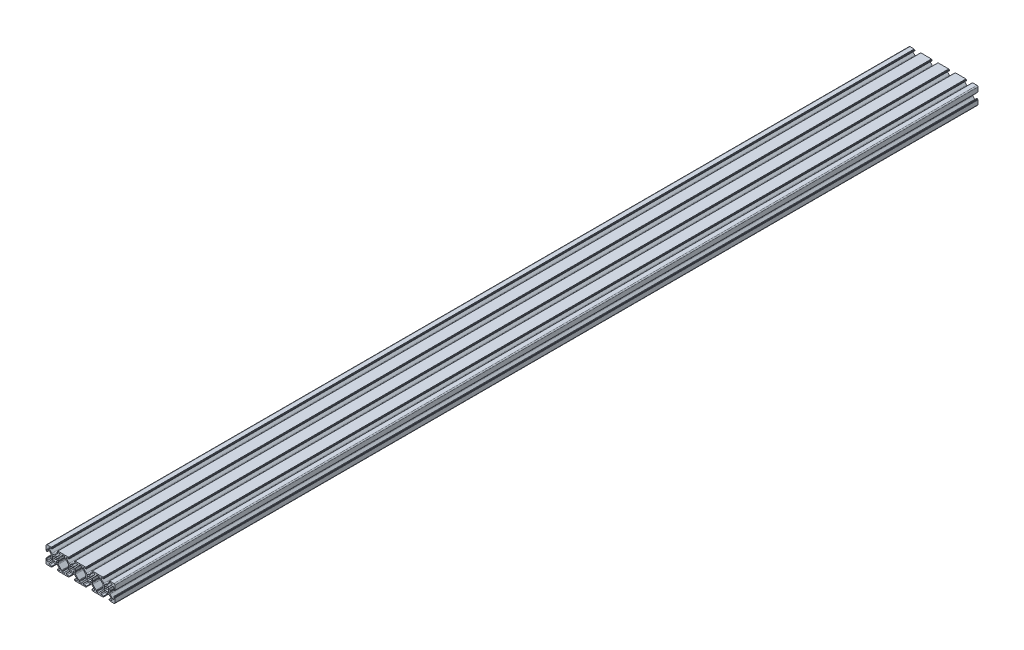
SolidWorks part; units mm, degrees
material "6063-T5"
ref_plane "Ön Düzlem" through (0, 0, 0) normal (0, 0, 1) x (1, 0, 0)
ref_plane "Üst Düzlem" through (0, 0, 0) normal (0, 1, 0) x (1, 0, 0)
ref_plane "Sağ Düzlem" through (0, 0, 0) normal (1, 0, 0) x (0, 0, -1)
sketch "Model" plane through (0, 0, 0) normal (0, 0, 1) x (1, 0, 0)
  line L0 (-8.8, -10) -> (-3.95, -10)
  line L1 (-3.95, -10) -> (-3.95, -9.5)
  line L2 (-3.95, -9.5) -> (-3.1475, -9.5)
  line L3 (-3.1475, -9.5) -> (-3.1475, -8.6)
  line L4 (-3.1475, -8.6) -> (-5.6787, -8.6)
  line L5 (-6.2444, -7.2343) -> (-3.1787, -4.1687)
  line L6 (-0.29, -4.19) -> (0, -3.9)
  line L7 (0, -3.9) -> (0.29, -4.19)
  line L8 (3.1768, -4.1667) -> (6.2444, -7.2343)
  line L9 (5.6787, -8.6) -> (3.1475, -8.6)
  line L10 (3.1475, -8.6) -> (3.1475, -9.5)
  line L11 (3.1475, -9.5) -> (3.95, -9.5)
  line L12 (3.95, -9.5) -> (3.95, -10)
  line L13 (3.95, -10) -> (16.05, -10)
  line L14 (16.05, -10) -> (16.05, -9.5)
  line L15 (16.05, -9.5) -> (16.8525, -9.5)
  line L16 (16.8525, -9.5) -> (16.8525, -8.6)
  line L17 (16.8525, -8.6) -> (14.3213, -8.6)
  line L18 (13.7556, -7.2343) -> (16.8213, -4.1687)
  line L19 (19.71, -4.19) -> (20, -3.9)
  line L20 (20, -3.9) -> (20.29, -4.19)
  line L21 (23.1768, -4.1667) -> (26.2444, -7.2343)
  line L22 (25.6787, -8.6) -> (23.1475, -8.6)
  line L23 (23.1475, -8.6) -> (23.1475, -9.5)
  line L24 (23.1475, -9.5) -> (23.95, -9.5)
  line L25 (23.95, -9.5) -> (23.95, -10)
  line L26 (23.95, -10) -> (36.05, -10)
  line L27 (36.05, -10) -> (36.05, -9.5)
  line L28 (36.05, -9.5) -> (36.8525, -9.5)
  line L29 (36.8525, -9.5) -> (36.8525, -8.6)
  line L30 (36.8525, -8.6) -> (34.3213, -8.6)
  line L31 (33.7556, -7.2343) -> (36.8213, -4.1687)
  line L32 (39.71, -4.19) -> (40, -3.9)
  line L33 (40, -3.9) -> (40.29, -4.19)
  line L34 (43.1768, -4.1667) -> (46.2444, -7.2343)
  line L35 (45.6787, -8.6) -> (43.1475, -8.6)
  line L36 (43.1475, -8.6) -> (43.1475, -9.5)
  line L37 (43.1475, -9.5) -> (43.95, -9.5)
  line L38 (43.95, -9.5) -> (43.95, -10)
  line L39 (43.95, -10) -> (56.05, -10)
  line L40 (56.05, -10) -> (56.05, -9.5)
  line L41 (56.05, -9.5) -> (56.8525, -9.5)
  line L42 (56.8525, -9.5) -> (56.8525, -8.6)
  line L43 (56.8525, -8.6) -> (54.3213, -8.6)
  line L44 (53.7556, -7.2343) -> (56.8213, -4.1687)
  line L45 (59.71, -4.19) -> (60, -3.9)
  line L46 (60, -3.9) -> (60.29, -4.19)
  line L47 (63.1768, -4.1667) -> (66.2444, -7.2343)
  line L48 (65.6787, -8.6) -> (63.1475, -8.6)
  line L49 (63.1475, -8.6) -> (63.1475, -9.5)
  line L50 (63.1475, -9.5) -> (63.95, -9.5)
  line L51 (63.95, -9.5) -> (63.95, -10)
  line L52 (63.95, -10) -> (68.8, -10)
  line L53 (70, -8.8) -> (70, -3.95)
  line L54 (70, -3.95) -> (69.5, -3.95)
  line L55 (69.5, -3.95) -> (69.5, -3.1477)
  line L56 (69.5, -3.1477) -> (68.6, -3.1477)
  line L57 (68.6, -3.1477) -> (68.6, -5.6787)
  line L58 (67.2343, -6.2444) -> (64.1687, -3.1787)
  line L59 (64.19, -0.29) -> (63.9, 0)
  line L60 (63.9, 0) -> (64.19, 0.29)
  line L61 (64.1667, 3.1768) -> (67.2343, 6.2444)
  line L62 (68.6, 5.6787) -> (68.6, 3.1475)
  line L63 (68.6, 3.1475) -> (69.5, 3.1475)
  line L64 (69.5, 3.1475) -> (69.5, 3.95)
  line L65 (69.5, 3.95) -> (70, 3.95)
  line L66 (70, 3.95) -> (70, 8.8)
  line L67 (68.8, 10) -> (63.95, 10)
  line L68 (63.95, 10) -> (63.95, 9.5)
  line L69 (63.95, 9.5) -> (63.1475, 9.5)
  line L70 (63.1475, 9.5) -> (63.1475, 8.6)
  line L71 (63.1475, 8.6) -> (65.6787, 8.6)
  line L72 (66.2444, 7.2343) -> (63.1768, 4.1667)
  line L73 (60.29, 4.19) -> (60, 3.9)
  line L74 (60, 3.9) -> (59.71, 4.19)
  line L75 (56.8213, 4.1687) -> (53.7556, 7.2343)
  line L76 (54.3213, 8.6) -> (56.8525, 8.6)
  line L77 (56.8525, 8.6) -> (56.8525, 9.5)
  line L78 (56.8525, 9.5) -> (56.05, 9.5)
  line L79 (56.05, 9.5) -> (56.05, 10)
  line L80 (56.05, 10) -> (43.95, 10)
  line L81 (43.95, 10) -> (43.95, 9.5)
  line L82 (43.95, 9.5) -> (43.1475, 9.5)
  line L83 (43.1475, 9.5) -> (43.1475, 8.6)
  line L84 (43.1475, 8.6) -> (45.6787, 8.6)
  line L85 (46.2444, 7.2343) -> (43.1768, 4.1667)
  line L86 (40.29, 4.19) -> (40, 3.9)
  line L87 (40, 3.9) -> (39.71, 4.19)
  line L88 (36.8213, 4.1687) -> (33.7556, 7.2343)
  line L89 (34.3213, 8.6) -> (36.8525, 8.6)
  line L90 (36.8525, 8.6) -> (36.8525, 9.5)
  line L91 (36.8525, 9.5) -> (36.05, 9.5)
  line L92 (36.05, 9.5) -> (36.05, 10)
  line L93 (36.05, 10) -> (23.95, 10)
  line L94 (23.95, 10) -> (23.95, 9.5)
  line L95 (23.95, 9.5) -> (23.1475, 9.5)
  line L96 (23.1475, 9.5) -> (23.1475, 8.6)
  line L97 (23.1475, 8.6) -> (25.6787, 8.6)
  line L98 (26.2444, 7.2343) -> (23.1768, 4.1667)
  line L99 (20.29, 4.19) -> (20, 3.9)
  line L100 (20, 3.9) -> (19.71, 4.19)
  line L101 (16.8213, 4.1687) -> (13.7556, 7.2343)
  line L102 (14.3213, 8.6) -> (16.8525, 8.6)
  line L103 (16.8525, 8.6) -> (16.8525, 9.5)
  line L104 (16.8525, 9.5) -> (16.05, 9.5)
  line L105 (16.05, 9.5) -> (16.05, 10)
  line L106 (16.05, 10) -> (3.95, 10)
  line L107 (3.95, 10) -> (3.95, 9.5)
  line L108 (3.95, 9.5) -> (3.1475, 9.5)
  line L109 (3.1475, 9.5) -> (3.1475, 8.6)
  line L110 (3.1475, 8.6) -> (5.6787, 8.6)
  line L111 (6.2444, 7.2343) -> (3.1768, 4.1667)
  line L112 (0.29, 4.19) -> (0, 3.9)
  line L113 (0, 3.9) -> (-0.29, 4.19)
  line L114 (-3.1787, 4.1687) -> (-6.2444, 7.2343)
  line L115 (-5.6787, 8.6) -> (-3.1475, 8.6)
  line L116 (-3.1475, 8.6) -> (-3.1475, 9.5)
  line L117 (-3.1475, 9.5) -> (-3.95, 9.5)
  line L118 (-3.95, 9.5) -> (-3.95, 10)
  line L119 (-3.95, 10) -> (-8.8, 10)
  line L120 (-10, 8.8) -> (-10, 3.95)
  line L121 (-10, 3.95) -> (-9.5, 3.95)
  line L122 (-9.5, 3.95) -> (-9.5, 3.1475)
  line L123 (-9.5, 3.1475) -> (-8.6, 3.1475)
  line L124 (-8.6, 3.1475) -> (-8.6, 5.6787)
  line L125 (-7.2343, 6.2444) -> (-4.1667, 3.1768)
  line L126 (-4.19, 0.29) -> (-3.9, 0)
  line L127 (-3.9, 0) -> (-4.19, -0.29)
  line L128 (-4.1687, -3.1787) -> (-7.2343, -6.2444)
  line L129 (-8.6, -5.6787) -> (-8.6, -3.1475)
  line L130 (-8.6, -3.1475) -> (-9.5, -3.1475)
  line L131 (-9.5, -3.1475) -> (-9.5, -3.95)
  line L132 (-9.5, -3.95) -> (-10, -3.95)
  line L133 (-10, -3.95) -> (-10, -8.8)
  line L134 (62.1404, 1.2918) -> (62.4749, 1.6263)
  line L135 (61.6263, 2.4749) -> (61.2918, 2.1404)
  line L136 (58.7082, 2.1404) -> (58.3737, 2.4749)
  line L137 (57.5251, 1.6263) -> (57.8596, 1.2918)
  line L138 (57.8596, -1.2918) -> (57.5251, -1.6263)
  line L139 (58.3737, -2.4749) -> (58.7082, -2.1404)
  line L140 (61.2918, -2.1404) -> (61.6263, -2.4749)
  line L141 (62.4749, -1.6263) -> (62.1404, -1.2918)
  line L142 (55.8342, -3.1759) -> (51.9899, -7.0201)
  line L143 (51.6971, -7.7272) -> (51.6971, -8.1)
  line L144 (51.1971, -8.6) -> (48.8029, -8.6)
  line L145 (48.3029, -8.1) -> (48.3029, -7.7272)
  line L146 (48.0101, -7.0201) -> (44.1658, -3.1759)
  line L147 (44.19, -0.29) -> (43.9, 0)
  line L148 (43.9, 0) -> (44.19, 0.29)
  line L149 (44.1658, 3.1759) -> (48.0101, 7.0201)
  line L150 (48.3029, 7.7272) -> (48.3029, 8.1)
  line L151 (48.8029, 8.6) -> (51.1971, 8.6)
  line L152 (51.6971, 8.1) -> (51.6971, 7.7272)
  line L153 (51.9899, 7.0201) -> (55.8342, 3.1759)
  line L154 (55.81, 0.29) -> (56.1, 0)
  line L155 (56.1, 0) -> (55.81, -0.29)
  line L156 (-2.1404, 1.2918) -> (-2.4749, 1.6263)
  line L157 (-1.6263, 2.4749) -> (-1.2918, 2.1404)
  line L158 (1.2918, 2.1404) -> (1.6263, 2.4749)
  line L159 (2.4749, 1.6263) -> (2.1404, 1.2918)
  line L160 (2.1404, -1.2918) -> (2.4749, -1.6263)
  line L161 (1.6263, -2.4749) -> (1.2918, -2.1404)
  line L162 (-1.2918, -2.1404) -> (-1.6263, -2.4749)
  line L163 (-2.4749, -1.6263) -> (-2.1404, -1.2918)
  line L164 (4.1658, -3.1759) -> (8.0101, -7.0201)
  line L165 (8.3029, -7.7272) -> (8.3029, -8.1)
  line L166 (8.8029, -8.6) -> (11.1971, -8.6)
  line L167 (11.6971, -8.1) -> (11.6971, -7.7272)
  line L168 (11.9899, -7.0201) -> (15.8342, -3.1759)
  line L169 (15.81, -0.29) -> (16.1, 0)
  line L170 (16.1, 0) -> (15.81, 0.29)
  line L171 (15.8342, 3.1759) -> (11.9899, 7.0201)
  line L172 (11.6971, 7.7272) -> (11.6971, 8.1)
  line L173 (11.1971, 8.6) -> (8.8029, 8.6)
  line L174 (8.3029, 8.1) -> (8.3029, 7.7272)
  line L175 (8.0101, 7.0201) -> (4.1658, 3.1759)
  line L176 (4.19, 0.29) -> (3.9, 0)
  line L177 (3.9, 0) -> (4.19, -0.29)
  line L178 (17.8596, 1.2918) -> (17.5251, 1.6263)
  line L179 (18.3737, 2.4749) -> (18.7082, 2.1404)
  line L180 (21.2918, 2.1404) -> (21.6263, 2.4749)
  line L181 (22.4749, 1.6263) -> (22.1404, 1.2918)
  line L182 (22.1404, -1.2918) -> (22.4749, -1.6263)
  line L183 (21.6263, -2.4749) -> (21.2918, -2.1404)
  line L184 (18.7082, -2.1404) -> (18.3737, -2.4749)
  line L185 (17.5251, -1.6263) -> (17.8596, -1.2918)
  line L186 (37.8596, 1.2918) -> (37.5251, 1.6263)
  line L187 (38.3737, 2.4749) -> (38.7082, 2.1404)
  line L188 (41.2918, 2.1404) -> (41.6263, 2.4749)
  line L189 (42.4749, 1.6263) -> (42.1404, 1.2918)
  line L190 (42.1404, -1.2918) -> (42.4749, -1.6263)
  line L191 (41.6263, -2.4749) -> (41.2918, -2.1404)
  line L192 (38.7082, -2.1404) -> (38.3737, -2.4749)
  line L193 (37.5251, -1.6263) -> (37.8596, -1.2918)
  line L194 (24.1658, -3.1759) -> (28.0101, -7.0201)
  line L195 (28.3029, -7.7272) -> (28.3029, -8.1)
  line L196 (28.8029, -8.6) -> (31.1971, -8.6)
  line L197 (31.6971, -8.1) -> (31.6971, -7.7272)
  line L198 (31.9899, -7.0201) -> (35.8342, -3.1759)
  line L199 (35.81, -0.29) -> (36.1, 0)
  line L200 (36.1, 0) -> (35.81, 0.29)
  line L201 (35.8342, 3.1759) -> (31.9899, 7.0201)
  line L202 (31.6971, 7.7272) -> (31.6971, 8.1)
  line L203 (31.1971, 8.6) -> (28.8029, 8.6)
  line L204 (28.3029, 8.1) -> (28.3029, 7.7272)
  line L205 (28.0101, 7.0201) -> (24.1658, 3.1759)
  line L206 (24.19, 0.29) -> (23.9, 0)
  line L207 (23.9, 0) -> (24.19, -0.29)
  arc A0 (-6.2444, -7.2343) -> (-5.6787, -8.6) centre (-5.6787, -7.8) ccw
  arc A1 (-1.6394, -3.8668) -> (-3.1787, -4.1687) centre (-2.1845, -5.1629) ccw
  arc A2 (-1.6394, -3.8668) -> (-0.29, -4.19) centre (0, 0) ccw
  arc A3 (0.29, -4.19) -> (1.6394, -3.8668) centre (0, 0) ccw
  arc A4 (3.1768, -4.1667) -> (1.6394, -3.8668) centre (2.1855, -5.1581) ccw
  arc A5 (5.6787, -8.6) -> (6.2444, -7.2343) centre (5.6787, -7.8) ccw
  arc A6 (13.7556, -7.2343) -> (14.3213, -8.6) centre (14.3213, -7.8) ccw
  arc A7 (18.3606, -3.8668) -> (16.8213, -4.1687) centre (17.8155, -5.1629) ccw
  arc A8 (18.3606, -3.8668) -> (19.71, -4.19) centre (20, 0) ccw
  arc A9 (20.29, -4.19) -> (21.6394, -3.8668) centre (20, 0) ccw
  arc A10 (23.1768, -4.1667) -> (21.6394, -3.8668) centre (22.1855, -5.1581) ccw
  arc A11 (25.6787, -8.6) -> (26.2444, -7.2343) centre (25.6787, -7.8) ccw
  arc A12 (33.7556, -7.2343) -> (34.3213, -8.6) centre (34.3213, -7.8) ccw
  arc A13 (38.3606, -3.8668) -> (36.8213, -4.1687) centre (37.8155, -5.1629) ccw
  arc A14 (38.3606, -3.8668) -> (39.71, -4.19) centre (40, 0) ccw
  arc A15 (40.29, -4.19) -> (41.6394, -3.8668) centre (40, 0) ccw
  arc A16 (43.1768, -4.1667) -> (41.6394, -3.8668) centre (42.1855, -5.1581) ccw
  arc A17 (45.6787, -8.6) -> (46.2444, -7.2343) centre (45.6787, -7.8) ccw
  arc A18 (53.7556, -7.2343) -> (54.3213, -8.6) centre (54.3213, -7.8) ccw
  arc A19 (58.3606, -3.8668) -> (56.8213, -4.1687) centre (57.8155, -5.1629) ccw
  arc A20 (58.3606, -3.8668) -> (59.71, -4.19) centre (60, 0) ccw
  arc A21 (60.29, -4.19) -> (61.6394, -3.8668) centre (60, 0) ccw
  arc A22 (63.1768, -4.1667) -> (61.6394, -3.8668) centre (62.1855, -5.1581) ccw
  arc A23 (65.6787, -8.6) -> (66.2444, -7.2343) centre (65.6787, -7.8) ccw
  arc A24 (68.8, -10) -> (70, -8.8) centre (68.8, -8.8) ccw
  arc A25 (67.2343, -6.2444) -> (68.6, -5.6787) centre (67.8, -5.6787) ccw
  arc A26 (63.8668, -1.6394) -> (64.1687, -3.1787) centre (65.1629, -2.1845) ccw
  arc A27 (63.8668, -1.6394) -> (64.19, -0.29) centre (60, 0) ccw
  arc A28 (64.19, 0.29) -> (63.8668, 1.6394) centre (60, 0) ccw
  arc A29 (64.1667, 3.1768) -> (63.8668, 1.6394) centre (65.1581, 2.1855) ccw
  arc A30 (68.6, 5.6787) -> (67.2343, 6.2444) centre (67.8, 5.6787) ccw
  arc A31 (70, 8.8) -> (68.8, 10) centre (68.8, 8.8) ccw
  arc A32 (66.2444, 7.2343) -> (65.6787, 8.6) centre (65.6787, 7.8) ccw
  arc A33 (61.6394, 3.8668) -> (63.1768, 4.1667) centre (62.1855, 5.1581) ccw
  arc A34 (61.6394, 3.8668) -> (60.29, 4.19) centre (60, 0) ccw
  arc A35 (59.71, 4.19) -> (58.3606, 3.8668) centre (60, 0) ccw
  arc A36 (56.8213, 4.1687) -> (58.3606, 3.8668) centre (57.8155, 5.1629) ccw
  arc A37 (54.3213, 8.6) -> (53.7556, 7.2343) centre (54.3213, 7.8) ccw
  arc A38 (46.2444, 7.2343) -> (45.6787, 8.6) centre (45.6787, 7.8) ccw
  arc A39 (41.6394, 3.8668) -> (43.1768, 4.1667) centre (42.1855, 5.1581) ccw
  arc A40 (41.6394, 3.8668) -> (40.29, 4.19) centre (40, 0) ccw
  arc A41 (39.71, 4.19) -> (38.3606, 3.8668) centre (40, 0) ccw
  arc A42 (36.8213, 4.1687) -> (38.3606, 3.8668) centre (37.8155, 5.1629) ccw
  arc A43 (34.3213, 8.6) -> (33.7556, 7.2343) centre (34.3213, 7.8) ccw
  arc A44 (26.2444, 7.2343) -> (25.6787, 8.6) centre (25.6787, 7.8) ccw
  arc A45 (21.6394, 3.8668) -> (23.1768, 4.1667) centre (22.1855, 5.1581) ccw
  arc A46 (21.6394, 3.8668) -> (20.29, 4.19) centre (20, 0) ccw
  arc A47 (19.71, 4.19) -> (18.3606, 3.8668) centre (20, 0) ccw
  arc A48 (16.8213, 4.1687) -> (18.3606, 3.8668) centre (17.8155, 5.1629) ccw
  arc A49 (14.3213, 8.6) -> (13.7556, 7.2343) centre (14.3213, 7.8) ccw
  arc A50 (6.2444, 7.2343) -> (5.6787, 8.6) centre (5.6787, 7.8) ccw
  arc A51 (1.6394, 3.8668) -> (3.1768, 4.1667) centre (2.1855, 5.1581) ccw
  arc A52 (1.6394, 3.8668) -> (0.29, 4.19) centre (0, 0) ccw
  arc A53 (-0.29, 4.19) -> (-1.6394, 3.8668) centre (0, 0) ccw
  arc A54 (-3.1787, 4.1687) -> (-1.6394, 3.8668) centre (-2.1845, 5.1629) ccw
  arc A55 (-5.6787, 8.6) -> (-6.2444, 7.2343) centre (-5.6787, 7.8) ccw
  arc A56 (-8.8, 10) -> (-10, 8.8) centre (-8.8, 8.8) ccw
  arc A57 (-7.2343, 6.2444) -> (-8.6, 5.6787) centre (-7.8, 5.6787) ccw
  arc A58 (-3.8668, 1.6394) -> (-4.1667, 3.1768) centre (-5.1581, 2.1855) ccw
  arc A59 (-3.8668, 1.6394) -> (-4.19, 0.29) centre (0, 0) ccw
  arc A60 (-4.19, -0.29) -> (-3.8668, -1.6394) centre (0, 0) ccw
  arc A61 (-4.1687, -3.1787) -> (-3.8668, -1.6394) centre (-5.1629, -2.1845) ccw
  arc A62 (-8.6, -5.6787) -> (-7.2343, -6.2444) centre (-7.8, -5.6787) ccw
  arc A63 (-10, -8.8) -> (-8.8, -10) centre (-8.8, -8.8) ccw
  arc A64 (51.9899, -7.0201) -> (51.6971, -7.7272) centre (52.6971, -7.7272) ccw
  arc A65 (51.1971, -8.6) -> (51.6971, -8.1) centre (51.1971, -8.1) ccw
  arc A66 (48.3029, -8.1) -> (48.8029, -8.6) centre (48.8029, -8.1) ccw
  arc A67 (48.3029, -7.7272) -> (48.0101, -7.0201) centre (47.3029, -7.7272) ccw
  arc A68 (43.8668, -1.6394) -> (44.1658, -3.1759) centre (45.1558, -2.1859) ccw
  arc A69 (43.8668, -1.6394) -> (44.19, -0.29) centre (40, 0) ccw
  arc A70 (44.19, 0.29) -> (43.8668, 1.6394) centre (40, 0) ccw
  arc A71 (44.1658, 3.1759) -> (43.8668, 1.6394) centre (45.1558, 2.1859) ccw
  arc A72 (48.0101, 7.0201) -> (48.3029, 7.7272) centre (47.3029, 7.7272) ccw
  arc A73 (48.8029, 8.6) -> (48.3029, 8.1) centre (48.8029, 8.1) ccw
  arc A74 (51.6971, 8.1) -> (51.1971, 8.6) centre (51.1971, 8.1) ccw
  arc A75 (51.6971, 7.7272) -> (51.9899, 7.0201) centre (52.6971, 7.7272) ccw
  arc A76 (56.1332, 1.6394) -> (55.8342, 3.1759) centre (54.8442, 2.1859) ccw
  arc A77 (56.1332, 1.6394) -> (55.81, 0.29) centre (60, 0) ccw
  arc A78 (55.81, -0.29) -> (56.1332, -1.6394) centre (60, 0) ccw
  arc A79 (55.8342, -3.1759) -> (56.1332, -1.6394) centre (54.8442, -2.1859) ccw
  arc A80 (8.3029, -7.7272) -> (8.0101, -7.0201) centre (7.3029, -7.7272) ccw
  arc A81 (8.3029, -8.1) -> (8.8029, -8.6) centre (8.8029, -8.1) ccw
  arc A82 (11.1971, -8.6) -> (11.6971, -8.1) centre (11.1971, -8.1) ccw
  arc A83 (11.9899, -7.0201) -> (11.6971, -7.7272) centre (12.6971, -7.7272) ccw
  arc A84 (15.8342, -3.1759) -> (16.1332, -1.6394) centre (14.8442, -2.1859) ccw
  arc A85 (15.81, -0.29) -> (16.1332, -1.6394) centre (20, 0) ccw
  arc A86 (16.1332, 1.6394) -> (15.81, 0.29) centre (20, 0) ccw
  arc A87 (16.1332, 1.6394) -> (15.8342, 3.1759) centre (14.8442, 2.1859) ccw
  arc A88 (11.6971, 7.7272) -> (11.9899, 7.0201) centre (12.6971, 7.7272) ccw
  arc A89 (11.6971, 8.1) -> (11.1971, 8.6) centre (11.1971, 8.1) ccw
  arc A90 (8.8029, 8.6) -> (8.3029, 8.1) centre (8.8029, 8.1) ccw
  arc A91 (8.0101, 7.0201) -> (8.3029, 7.7272) centre (7.3029, 7.7272) ccw
  arc A92 (4.1658, 3.1759) -> (3.8668, 1.6394) centre (5.1558, 2.1859) ccw
  arc A93 (4.19, 0.29) -> (3.8668, 1.6394) centre (0, 0) ccw
  arc A94 (3.8668, -1.6394) -> (4.19, -0.29) centre (0, 0) ccw
  arc A95 (3.8668, -1.6394) -> (4.1658, -3.1759) centre (5.1558, -2.1859) ccw
  arc A96 (28.3029, -7.7272) -> (28.0101, -7.0201) centre (27.3029, -7.7272) ccw
  arc A97 (28.3029, -8.1) -> (28.8029, -8.6) centre (28.8029, -8.1) ccw
  arc A98 (31.1971, -8.6) -> (31.6971, -8.1) centre (31.1971, -8.1) ccw
  arc A99 (31.9899, -7.0201) -> (31.6971, -7.7272) centre (32.6971, -7.7272) ccw
  arc A100 (35.8342, -3.1759) -> (36.1332, -1.6394) centre (34.8442, -2.1859) ccw
  arc A101 (35.81, -0.29) -> (36.1332, -1.6394) centre (40, 0) ccw
  arc A102 (36.1332, 1.6394) -> (35.81, 0.29) centre (40, 0) ccw
  arc A103 (36.1332, 1.6394) -> (35.8342, 3.1759) centre (34.8442, 2.1859) ccw
  arc A104 (31.6971, 7.7272) -> (31.9899, 7.0201) centre (32.6971, 7.7272) ccw
  arc A105 (31.6971, 8.1) -> (31.1971, 8.6) centre (31.1971, 8.1) ccw
  arc A106 (28.8029, 8.6) -> (28.3029, 8.1) centre (28.8029, 8.1) ccw
  arc A107 (28.0101, 7.0201) -> (28.3029, 7.7272) centre (27.3029, 7.7272) ccw
  arc A108 (24.1658, 3.1759) -> (23.8668, 1.6394) centre (25.1558, 2.1859) ccw
  arc A109 (24.19, 0.29) -> (23.8668, 1.6394) centre (20, 0) ccw
  arc A110 (23.8668, -1.6394) -> (24.19, -0.29) centre (20, 0) ccw
  arc A111 (23.8668, -1.6394) -> (24.1658, -3.1759) centre (25.1558, -2.1859) ccw
  arc A112 (62.4749, 1.6263) -> (61.6263, 2.4749) centre (62.0506, 2.0506) ccw
  arc A113 (61.2918, 2.1404) -> (58.7082, 2.1404) centre (60, 0) ccw
  arc A114 (58.3737, 2.4749) -> (57.5251, 1.6263) centre (57.9494, 2.0506) ccw
  arc A115 (57.8596, 1.2918) -> (57.8596, -1.2918) centre (60, 0) ccw
  arc A116 (57.5251, -1.6263) -> (58.3737, -2.4749) centre (57.9494, -2.0506) ccw
  arc A117 (58.7082, -2.1404) -> (61.2918, -2.1404) centre (60, 0) ccw
  arc A118 (61.6263, -2.4749) -> (62.4749, -1.6263) centre (62.0506, -2.0506) ccw
  arc A119 (62.1404, -1.2918) -> (62.1404, 1.2918) centre (60, 0) ccw
  arc A120 (-1.6263, 2.4749) -> (-2.4749, 1.6263) centre (-2.0506, 2.0506) ccw
  arc A121 (1.2918, 2.1404) -> (-1.2918, 2.1404) centre (0, 0) ccw
  arc A122 (2.4749, 1.6263) -> (1.6263, 2.4749) centre (2.0506, 2.0506) ccw
  arc A123 (2.1404, -1.2918) -> (2.1404, 1.2918) centre (0, 0) ccw
  arc A124 (1.6263, -2.4749) -> (2.4749, -1.6263) centre (2.0506, -2.0506) ccw
  arc A125 (-1.2918, -2.1404) -> (1.2918, -2.1404) centre (0, 0) ccw
  arc A126 (-2.4749, -1.6263) -> (-1.6263, -2.4749) centre (-2.0506, -2.0506) ccw
  arc A127 (-2.1404, 1.2918) -> (-2.1404, -1.2918) centre (0, 0) ccw
  arc A128 (18.3737, 2.4749) -> (17.5251, 1.6263) centre (17.9494, 2.0506) ccw
  arc A129 (21.2918, 2.1404) -> (18.7082, 2.1404) centre (20, 0) ccw
  arc A130 (22.4749, 1.6263) -> (21.6263, 2.4749) centre (22.0506, 2.0506) ccw
  arc A131 (22.1404, -1.2918) -> (22.1404, 1.2918) centre (20, 0) ccw
  arc A132 (21.6263, -2.4749) -> (22.4749, -1.6263) centre (22.0506, -2.0506) ccw
  arc A133 (18.7082, -2.1404) -> (21.2918, -2.1404) centre (20, 0) ccw
  arc A134 (17.5251, -1.6263) -> (18.3737, -2.4749) centre (17.9494, -2.0506) ccw
  arc A135 (17.8596, 1.2918) -> (17.8596, -1.2918) centre (20, 0) ccw
  arc A136 (38.3737, 2.4749) -> (37.5251, 1.6263) centre (37.9494, 2.0506) ccw
  arc A137 (41.2918, 2.1404) -> (38.7082, 2.1404) centre (40, 0) ccw
  arc A138 (42.4749, 1.6263) -> (41.6263, 2.4749) centre (42.0506, 2.0506) ccw
  arc A139 (42.1404, -1.2918) -> (42.1404, 1.2918) centre (40, 0) ccw
  arc A140 (41.6263, -2.4749) -> (42.4749, -1.6263) centre (42.0506, -2.0506) ccw
  arc A141 (38.7082, -2.1404) -> (41.2918, -2.1404) centre (40, 0) ccw
  arc A142 (37.5251, -1.6263) -> (38.3737, -2.4749) centre (37.9494, -2.0506) ccw
  arc A143 (37.8596, 1.2918) -> (37.8596, -1.2918) centre (40, 0) ccw
extrude "Yükseklik-Ekstrüzyon1" add sketch "Model" against normal blind 1000
